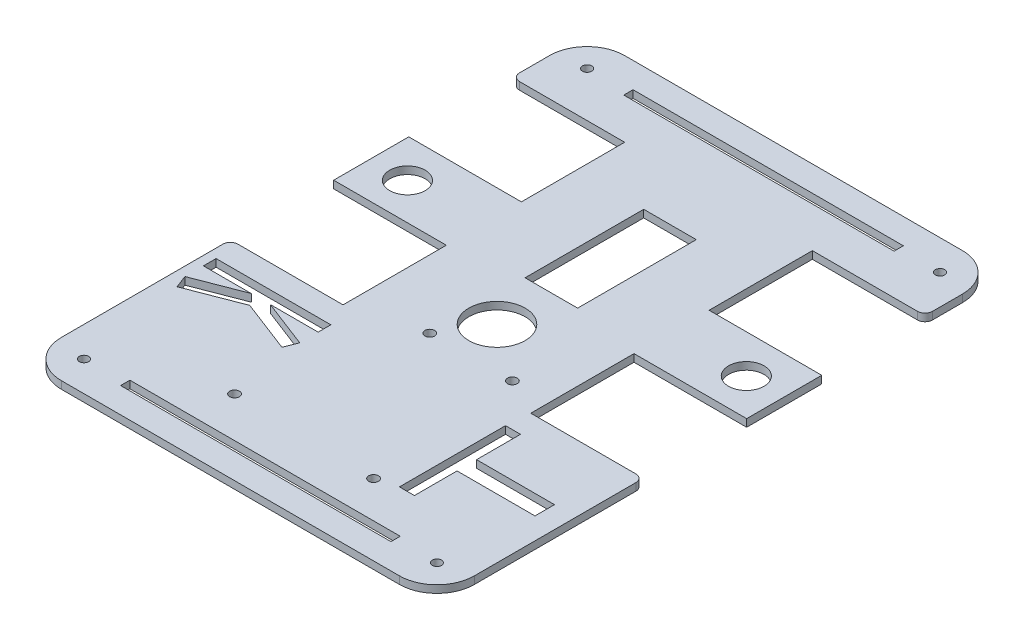
SolidWorks part; units mm, degrees
material "ABS"
ref_plane "Front Plane" through (0, 0, 0) normal (0, 0, 1) x (1, 0, 0)
ref_plane "Top Plane" through (0, 0, 0) normal (0, 1, 0) x (1, 0, 0)
ref_plane "Right Plane" through (0, 0, 0) normal (1, 0, 0) x (0, 0, -1)
sketch "Sketch2" plane through (0, 0, 0) normal (0, 1, 0) x (1, 0, 0)
  line L0 (-148.7583, 0) -> (98.0966, 0) construction
  line L1 (-69.85, -95.25) -> (69.85, -95.25)
  line L2 (-69.85, -95.25) -> (-69.85, 95.25)
  line L3 (-69.85, 95.25) -> (69.85, 95.25)
  line L4 (69.85, -95.25) -> (69.85, 95.25)
  line L5 (-69.85, -95.25) -> (69.85, 95.25) construction
  line L6 (-69.85, 95.25) -> (69.85, -95.25) construction
  line L7 (0, 121.1686) -> (0, -125.6862) construction
  point P0 (0, 0)
  dimension "D1" = 190.5
  dimension "D2" = 139.7
extrude "Base Plate" add sketch "Sketch2" along normal blind 2.54
sketch "Sketch4" plane through (0, 2.54, 0) normal (0, 1, 0) x (1, 0, 0)
  line L0 (0, -95.25) -> (0, 95.25) construction
  line L1 (-69.85, -95.25) -> (69.85, -95.25) construction
  line L2 (69.85, 95.25) -> (-69.85, 95.25) construction
  line L3 (-34.66, -69.85) -> (-34.66, -40.894) construction
  line L4 (-34.66, -40.894) -> (-58.79, -40.894) construction
  line L5 (-58.79, -40.894) -> (-58.79, -69.85) construction
  line L6 (-58.79, -69.85) -> (-34.66, -69.85) construction
  line L7 (69.85, -95.25) -> (69.85, 95.25) construction
  line L8 (-69.85, 95.25) -> (-69.85, -95.25) construction
  circle A0 centre (-58.79, -69.85) radius 1.8415
  circle A1 centre (-34.66, -69.85) radius 1.8415
  circle A2 centre (-34.66, -40.894) radius 1.8415
  circle A3 centre (-58.79, -40.894) radius 1.8415
  circle A4 centre (34.66, -69.85) radius 1.8415
  circle A5 centre (58.79, -69.85) radius 1.8415
  circle A6 centre (58.79, -40.894) radius 1.8415
  circle A7 centre (34.66, -40.894) radius 1.8415
  point P0 (-58.79, -69.85)
  point P1 (-58.79, -40.894)
  point P2 (-34.66, -40.894)
  point P3 (-34.66, -69.85)
  dimension "D4" = 3.683
  dimension "D1" = 28.956
  dimension "D2" = 24.13
  dimension "D3" = 11.06
  dimension "D5" = 25.4
sketch "Sketch5" plane through (0, 2.54, 0) normal (0, 1, 0) x (1, 0, 0)
  line L0 (-69.85, -25.4) -> (-31.75, -25.4)
  line L1 (-69.85, 95.25) -> (-69.85, -95.25) construction
  line L2 (-31.75, -25.4) -> (-31.75, 69.85)
  line L3 (-31.75, 69.85) -> (-69.85, 69.85)
  line L4 (-69.85, 69.85) -> (-69.85, -25.4)
  line L5 (-69.85, -95.25) -> (69.85, -95.25) construction
  line L6 (69.85, 95.25) -> (-69.85, 95.25) construction
  line L7 (0, -95.25) -> (0, 95.25) construction
  line L9 (31.75, 69.85) -> (69.85, 69.85)
  line L10 (31.75, -25.4) -> (31.75, 69.85)
  line L11 (69.85, -25.4) -> (31.75, -25.4)
  line L12 (69.85, 69.85) -> (69.85, -25.4)
  dimension "D1" = 25.4
  dimension "D2" = 95.25
  dimension "D3" = 38.1
extrude "Steering Wheels Holes" cut sketch "Sketch5" against normal blind 6.35
fillet "Fillet1" radius 12.7 4 edges at (69.85, 1.27, -95.25) (-69.85, 1.27, -95.25) (69.85, 1.27, 95.25) (-69.85, 1.27, 95.25)
fillet "Fillet2" radius 2.54 4 edges at (69.85, 1.27, -69.85) (69.85, 1.27, 25.4) (-69.85, 1.27, 25.4) (-69.85, 1.27, -69.85)
sketch "Sketch6" plane through (0, 2.54, 0) normal (0, 1, 0) x (1, 0, 0)
  line L0 (-69.85, -95.25) -> (-69.85, 95.25) construction
  line L1 (-69.85, -95.25) -> (69.85, -95.25) construction
  line L2 (0, -88.935) -> (0, 95.5267) construction
  line L3 (-69.85, -27.94) -> (69.85, -27.94) construction
  point P0 (-59.69, -85.09)
  point P12 (-59.69, 29.21)
  point P13 (59.69, -85.09)
  point P14 (59.69, 29.21)
  dimension "D1" = 10.16
  dimension "D2" = 10.16
sketch "Sketch15" plane through (0, 2.54, 0) normal (0, 1, 0) x (1, 0, 0)
  line L0 (-69.85, -95.25) -> (-69.85, 95.25) construction
  line L1 (-69.85, 95.25) -> (69.85, 95.25) construction
  line L2 (0, 95.25) -> (0, 49.0943) construction
  line L3 (0, 121.1686) -> (0, -125.6862) construction
  point P0 (-59.69, 85.09)
  point P5 (59.69, 85.09)
  dimension "D1" = 10.16
  dimension "D2" = 10.16
sketch "Sketch18" plane through (0, 2.54, 0) normal (0, 1, 0) x (1, 0, 0)
  line L0 (0, 95.25) -> (0, -95.25) construction
  line L1 (57.15, 95.25) -> (-57.15, 95.25) construction
  line L2 (-57.15, -95.25) -> (57.15, -95.25) construction
  line L3 (-24.003, -69.85) -> (78.9561, -69.85) construction
  circle A0 centre (-8.763, -19.05) radius 1.651
  circle A1 centre (19.177, -19.05) radius 1.651
  circle A2 centre (-24.003, -69.85) radius 1.651
  circle A3 centre (24.3097, -71.12) radius 1.651
  point P6 (-8.763, -19.05)
  point P7 (19.177, -19.05)
  point P8 (-24.003, -69.85)
  point P9 (24.257, -64.77)
  dimension "D7" = 3.302
  dimension "D1" = 52.07
  dimension "D2" = 1.27
  dimension "D3" = 5.08
  dimension "D4" = 27.94
  dimension "D5" = 15.24
  dimension "D6" = 50.8
  dimension "D8" = 114.3
extrude "Holes for Arduino UNO" cut sketch "Sketch18" against normal through all
sketch "Sketch20" plane through (0, 2.54, 0) normal (0, 1, 0) x (1, 0, 0)
  line L0 (0, 95.25) -> (0, -95.25) construction
  line L1 (57.15, 95.25) -> (-57.15, 95.25) construction
  line L2 (-57.15, -95.25) -> (57.15, -95.25) construction
  circle A0 centre (0, -5.08) radius 9.525
  dimension "D1" = 19.05
  dimension "D2" = 90.17
extrude "Cutout for motor wires" cut sketch "Sketch20" against normal through all
sketch "Sketch21" plane through (0, 2.54, 0) normal (0, 1, 0) x (1, 0, 0)
  line L0 (-31.75, 22.225) -> (31.75, 22.225) construction
  line L1 (-31.75, -25.4) -> (-31.75, 69.85) construction
  line L2 (31.75, 69.85) -> (31.75, -25.4) construction
  line L3 (0, 95.25) -> (0, -21.3651) construction
  line L4 (57.15, 95.25) -> (-57.15, 95.25) construction
  point P6 (-21.59, 22.225)
  point P12 (21.59, 22.225)
  dimension "D1" = 10.16
sketch "Sketch24" plane through (0, 2.54, 0) normal (0, 1, 0) x (1, 0, 0)
  line L0 (0, -95.25) -> (0, 95.25) construction
  line L1 (-57.15, -95.25) -> (57.15, -95.25) construction
  line L2 (57.15, 95.25) -> (-57.15, 95.25) construction
  line L3 (-69.85, 82.55) -> (-69.85, 72.39) construction
  circle A0 centre (-59.69, 85.09) radius 1.57
  circle A1 centre (-59.69, 85.09) radius 2.84
  dimension "D1" = 3.14
  dimension "D2" = 10.16
  dimension "D3" = 10.16
  dimension "D4" = 1.27
extrude "Cut-Extrude1" cut sketch "Sketch24" against normal blind 2.54 contours A0
mirror "Mirror1" about plane through (0, 0, 0) normal (1, 0, 0) of "Cut-Extrude1"
sketch "Sketch25" plane through (0, 2.54, 0) normal (0, 1, 0) x (1, 0, 0)
  line L0 (0, -95.25) -> (0, 95.25) construction
  line L1 (-57.15, -95.25) -> (57.15, -95.25) construction
  line L2 (57.15, 95.25) -> (-57.15, 95.25) construction
  line L3 (-69.85, -27.94) -> (-69.85, -82.55) construction
  circle A0 centre (-59.69, -85.09) radius 1.57
  circle A2 centre (59.69, -85.09) radius 1.57
  dimension "D1" = 3.14
  dimension "D4" = 3.14
  dimension "D2" = 10.16
  dimension "D3" = 10.16
extrude "Cut-Extrude3" cut sketch "Sketch25" against normal blind 2.54
sketch "Sketch27" plane through (0, 2.54, 0) normal (0, 1, 0) x (1, 0, 0)
  line L12 (0, -95.25) -> (0, 166.7066) construction
  line L13 (-57.15, -95.25) -> (57.15, -95.25) construction
  line L14 (-59.69, -87.93) -> (59.69, -87.93) construction
  line L15 (59.69, -82.25) -> (-59.69, -82.25) construction
  line L16 (-45.72, -86.66) -> (45.72, -86.66)
  line L17 (-46.99, -87.93) -> (46.99, -87.93)
  line L18 (-46.99, -87.93) -> (-46.99, -82.25)
  line L19 (-46.99, -82.25) -> (46.99, -82.25)
  line L20 (46.99, -87.93) -> (46.99, -82.25)
  line L21 (45.72, -86.66) -> (45.72, -83.52)
  line L22 (-45.72, -83.52) -> (45.72, -83.52)
  line L23 (-45.72, -86.66) -> (-45.72, -83.52)
  line L24 (-59.69, 82.25) -> (59.69, 82.25) construction
  line L25 (59.69, 87.93) -> (-59.69, 87.93) construction
  line L26 (-45.72, 86.66) -> (45.72, 86.66)
  line L27 (-46.99, 82.25) -> (46.99, 82.25)
  line L28 (-46.99, 82.25) -> (-46.99, 87.93)
  line L29 (-46.99, 87.93) -> (46.99, 87.93)
  line L30 (46.99, 82.25) -> (46.99, 87.93)
  line L31 (45.72, 83.52) -> (45.72, 86.66)
  line L32 (-45.72, 83.52) -> (45.72, 83.52)
  line L33 (-45.72, 83.52) -> (-45.72, 86.66)
  circle A8 centre (-59.69, -85.09) radius 2.84
  circle A9 centre (-59.69, -85.09) radius 1.57 construction
  circle A10 centre (59.69, -85.09) radius 2.84
  circle A11 centre (-59.69, 85.09) radius 2.84
  circle A12 centre (-59.69, 85.09) radius 1.57 construction
  circle A13 centre (59.69, 85.09) radius 2.84
  dimension "D1" = 1.27
  dimension "D5" = 1.27
  dimension "D6" = 12.7
  dimension "D7" = 12.7
  dimension "D2" = 12.7
  dimension "D3" = 12.7
  dimension "D4" = 1.27
  dimension "D8" = 1.27
extrude "Cut-Extrude4" cut sketch "Sketch27" against normal blind 2.54 contours L23 L16 L21 L22 | L26 L31 L32 L33
sketch "Sketch28" plane through (0, 2.54, 0) normal (0, 1, 0) x (1, 0, 0)
  line L0 (-31.75, 9.525) -> (-69.85, 9.525)
  line L1 (-31.75, -25.4) -> (-31.75, 69.85) construction
  line L2 (-69.85, 9.525) -> (-69.85, 34.925)
  line L3 (-69.85, 34.925) -> (-31.75, 34.925)
  line L4 (-31.75, 9.525) -> (-31.75, 34.925)
  line L5 (-69.85, -27.94) -> (-69.85, -82.55) construction
  point P6 (-31.75, 22.225)
  point P10 (-31.75, 22.225)
  dimension "D1" = 25.4
extrude "Boss-Extrude1" add sketch "Sketch28" against normal through all
mirror "Mirror2" about plane through (0, 0, 0) normal (1, 0, 0) of "Boss-Extrude1"
sketch "Sketch29" plane through (0, 0, 0) normal (0, -1, 0) x (1, 0, 0)
  line L0 (-69.85, -34.925) -> (-69.85, -9.525) construction
  circle A0 centre (-57.3106, -21.9452) radius 6
  dimension "D1" = 12
  dimension "D2" = 12.5394
extrude "Cut-Extrude5" cut sketch "Sketch29" against normal through all contours A0
mirror "Mirror3" about plane through (0, 0, 0) normal (1, 0, 0) of "Cut-Extrude5"
sketch "Sketch30" plane through (0, 0, 0) normal (0, -1, 0) x (1, 0, 0)
  line L0 (-57.3106, -21.9452) -> (57.3106, -21.9452) construction
  line L1 (8.89, -60.0452) -> (-8.89, -60.0452)
  line L2 (8.89, -60.0452) -> (8.89, -6.7052)
  line L3 (8.89, -6.7052) -> (-8.89, -6.7052)
  line L4 (-8.89, -60.0452) -> (-8.89, -6.7052)
  line L5 (8.89, -60.0452) -> (-8.89, -6.7052) construction
  line L6 (8.89, -6.7052) -> (-8.89, -60.0452) construction
  line L7 (0, 88.935) -> (0, -95.5267) construction
  line L8 (-8.89, -53.4412) -> (8.89, -53.4412)
  line L9 (-8.89, -13.3092) -> (8.89, -13.3092)
  point P0 (0, -33.3752)
  point P9 (0, -6.7052)
  dimension "D1" = 17.78
  dimension "D2" = 53.34
  dimension "D3" = 15.24
  dimension "D4" = 6.604
  dimension "D5" = 6.604
  dimension "D6" = 40.132
extrude "Cut-Extrude6" cut sketch "Sketch30" against normal through all contours L9 L4 L8 L2
sketch "Sketch31" plane through (0, 0, 0) normal (0, -1, 0) x (1, 0, 0)
  line L0 (-47.3732, 37.6063) -> (-47.3732, 54.7726) construction
  line L1 (-66.7828, 33.3147) -> (-27.9636, 33.3147)
  line L2 (-66.7828, 33.3147) -> (-66.7828, 37.6063)
  line L3 (-66.7828, 37.6063) -> (-50.5919, 37.6063)
  line L4 (-27.9636, 33.3147) -> (-27.9636, 37.6063)
  line L5 (-50.5919, 37.6063) -> (-66.7828, 43.8486)
  line L6 (-66.7828, 43.8486) -> (-65.1152, 48.1741)
  line L7 (-65.1152, 48.1741) -> (-47.3732, 41.3338)
  line L10 (-44.1545, 37.6063) -> (-27.9636, 43.8486)
  line L11 (-27.9636, 43.8486) -> (-29.6313, 48.1741)
  line L12 (-29.6313, 48.1741) -> (-47.3732, 41.3338)
  line L14 (-44.1545, 37.6063) -> (-27.9636, 37.6063)
  line L15 (31.1215, 33.3147) -> (36.1902, 33.3147)
  line L16 (36.1902, 33.3147) -> (36.1902, 48.1741)
  line L17 (36.1902, 48.1741) -> (62.5471, 48.1741)
  line L18 (62.5471, 48.1741) -> (62.5471, 54.7726)
  line L19 (62.5471, 54.7726) -> (36.1902, 54.7726)
  line L20 (36.1902, 54.7726) -> (36.1902, 69.2008)
  line L21 (36.1902, 69.2008) -> (31.1215, 69.2008)
  line L22 (31.1215, 69.2008) -> (31.1215, 33.3147)
extrude "Cut-Extrude7" cut sketch "Sketch31" against normal blind 2.54
